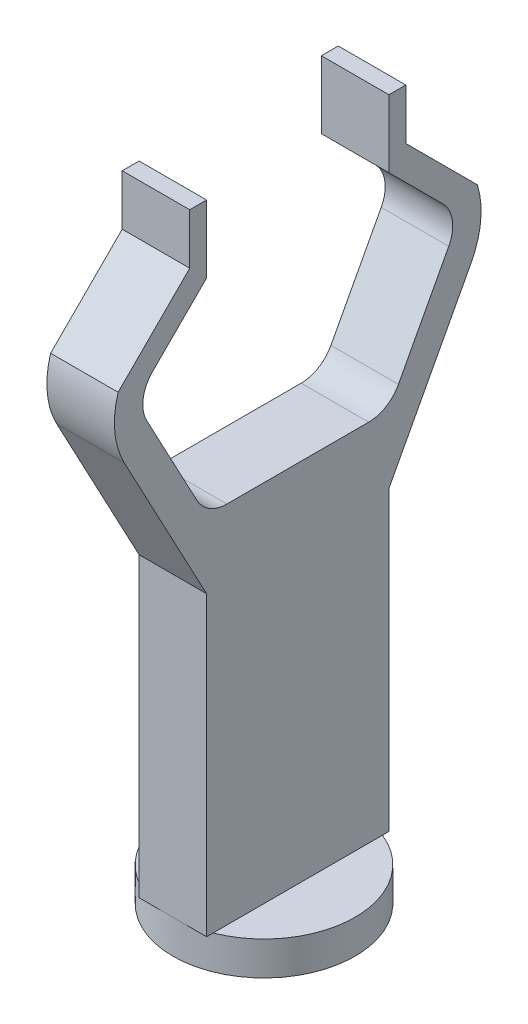
SolidWorks part; units mm, degrees
ref_plane "Front Plane" through (0, 0, 0) normal (0, 0, 1) x (1, 0, 0)
ref_plane "Top Plane" through (0, 0, 0) normal (0, 1, 0) x (1, 0, 0)
ref_plane "Right Plane" through (0, 0, 0) normal (1, 0, 0) x (0, 0, -1)
sketch "Sketch2" plane through (0, 0, 0) normal (0, 1, 0) x (1, 0, 0)
  circle A0 centre (0, 0) radius 27
  dimension "D1" = 54
extrude "Boss-Extrude1" add sketch "Sketch2" along normal blind 10
sketch "Sketch3" plane through (0, 0, 0) normal (1, 0, 0) x (0, 0, -1)
  line L0 (0, 118) -> (0, 199) construction
  line L1 (27, 10) -> (-27, 10)
  line L2 (27, 10) -> (27, 98)
  line L3 (27, 118) -> (-27, 118)
  line L4 (-27, 10) -> (-27, 98)
  line L5 (0, 199) -> (27, 199) construction
  line L6 (27, 199) -> (27, 179)
  line L7 (27, 179) -> (48.2132, 157.7868)
  line L8 (48.2132, 157.7868) -> (27, 118)
  line L9 (27, 199) -> (32, 199)
  line L10 (32, 199) -> (32, 184)
  line L11 (32, 184) -> (53.2132, 162.7868)
  line L12 (-27, 199) -> (-27, 179)
  line L13 (27, 98) -> (51.3689, 143.7056)
  line L14 (-32, 199) -> (-32, 184)
  line L15 (-27, 199) -> (-32, 199)
  line L16 (-27, 179) -> (-48.2132, 157.7868)
  line L17 (-32, 184) -> (-53.2132, 162.7868)
  line L18 (-48.2132, 157.7868) -> (-27, 118)
  line L19 (-27, 98) -> (-51.3689, 143.7056)
  arc A1 (51.3689, 143.7056) -> (53.2132, 162.7868) centre (29.3086, 155.4675) ccw
  arc A2 (-51.3689, 143.7056) -> (-53.2132, 162.7868) centre (-29.3086, 155.4675) cw
  dimension "D10" = 50
  dimension "D1" = 108
  dimension "D2" = 54
  dimension "D3" = 81
  dimension "D4" = 20
  dimension "D5" = 30
  dimension "D6" = 5
  dimension "D7" = 15
  dimension "D8" = 30
  dimension "D9" = 20
extrude "Boss-Extrude2" add sketch "Sketch3" along normal mid plane 20
fillet "Fillet1" radius 10 4 edges at (0, 118, -27) (0, 118, 27) (0, 157.7868, -48.2132) (0, 157.7868, 48.2132)
